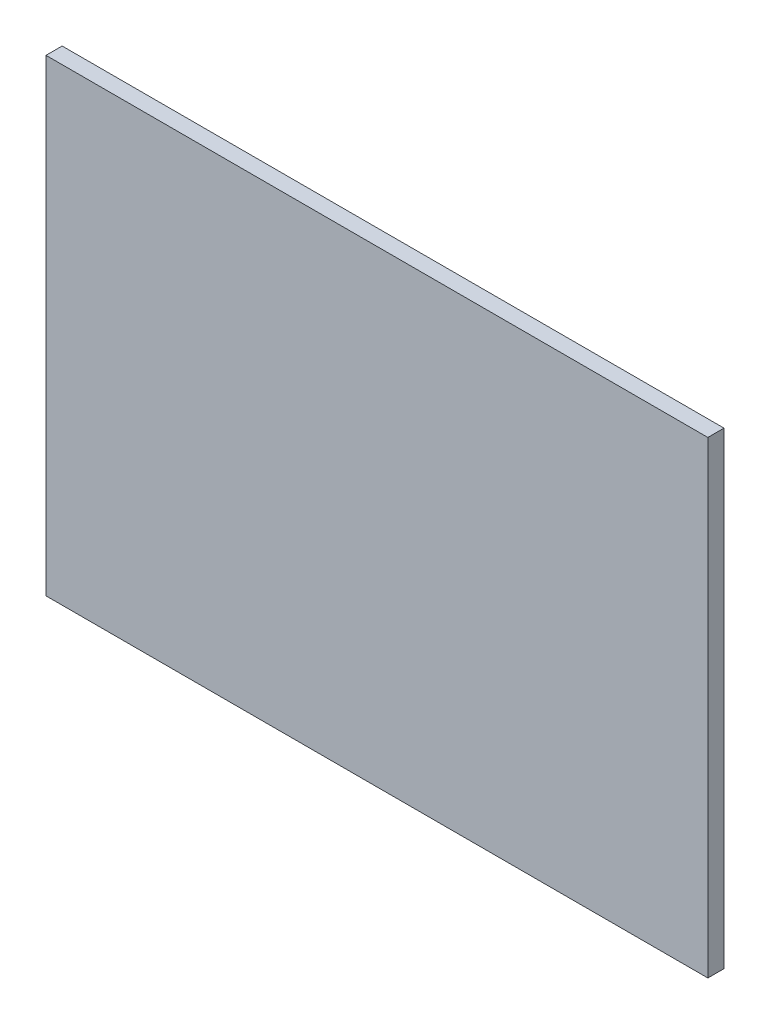
SolidWorks part; units mm, degrees
ref_plane "Plano frontal" through (0, 0, 0) normal (0, 0, 1) x (1, 0, 0)
ref_plane "Plano superior" through (0, 0, 0) normal (0, 1, 0) x (1, 0, 0)
ref_plane "Plano direito" through (0, 0, 0) normal (1, 0, 0) x (0, 0, -1)
sketch "Esboço1" plane through (0, 0, 0) normal (0, 0, 1) x (1, 0, 0)
  line L1 (-7.1084, 45.4625) -> (74.8916, 45.4625)
  line L2 (-7.1084, 45.4625) -> (-7.1084, -12.5375)
  line L3 (-7.1084, -12.5375) -> (74.8916, -12.5375)
  line L4 (74.8916, 45.4625) -> (74.8916, -12.5375)
  dimension "D1" = 82
  dimension "D2" = 58
extrude "Ressalto-extrusão1" add sketch "Esboço1" along normal blind 2
